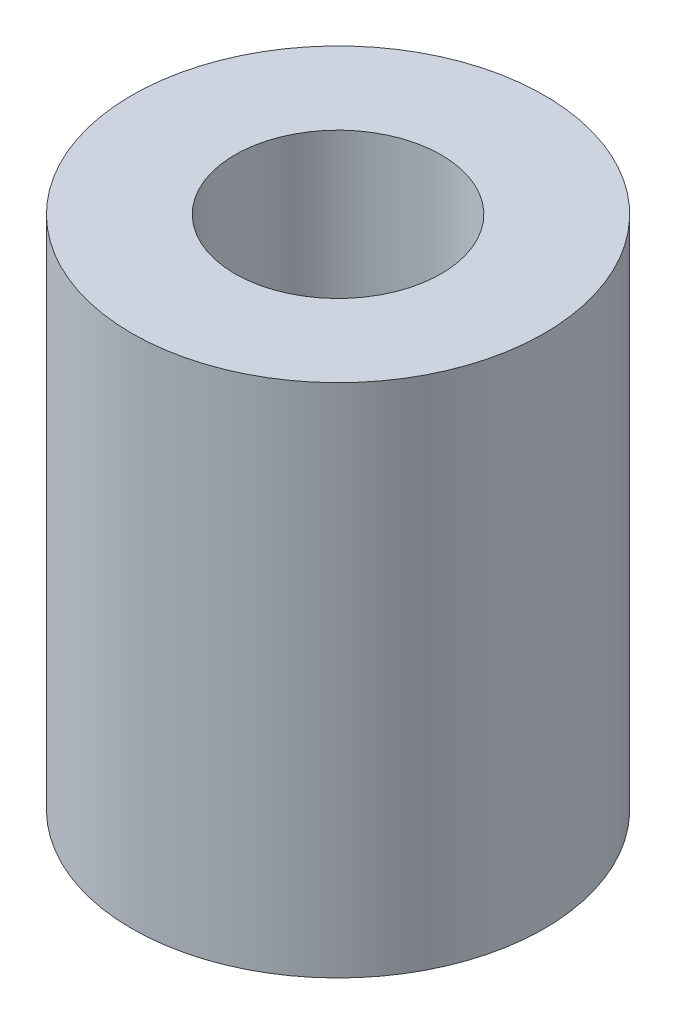
SolidWorks part; units mm, degrees
material "Custom Plastic"
ref_plane "Front Plane" through (0, 0, 0) normal (0, 0, 1) x (1, 0, 0)
ref_plane "Top Plane" through (0, 0, 0) normal (0, 1, 0) x (1, 0, 0)
ref_plane "Right Plane" through (0, 0, 0) normal (1, 0, 0) x (0, 0, -1)
sketch "Sketch1" plane through (0, 0, 0) normal (0, 1, 0) x (1, 0, 0)
  circle A0 centre (0, 0) radius 1
  circle A1 centre (0, 0) radius 2
  dimension "D1" = 2
  dimension "D2" = 4
extrude "Boss-Extrude1" add sketch "Sketch1" along normal blind 5
